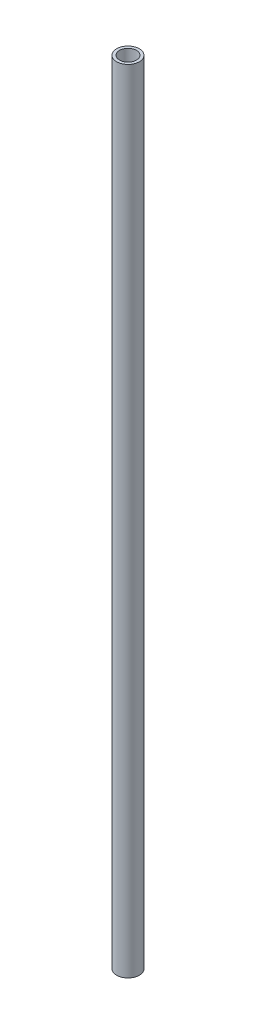
SolidWorks part; units mm, degrees
material "Thornel Mat VMA"
ref_plane "Front Plane" through (0, 0, 0) normal (0, 0, 1) x (1, 0, 0)
ref_plane "Top Plane" through (0, 0, 0) normal (0, 1, 0) x (1, 0, 0)
ref_plane "Right Plane" through (0, 0, 0) normal (1, 0, 0) x (0, 0, -1)
sketch "Sketch1" plane through (0, 0, 0) normal (0, 1, 0) x (1, 0, 0)
  circle A0 centre (0, 0) radius 3
  circle A1 centre (0, 0) radius 4
  dimension "D1" = 6
  dimension "D2" = 8
extrude "Boss-Extrude1" add sketch "Sketch1" along normal blind 280 contours A1 A0
